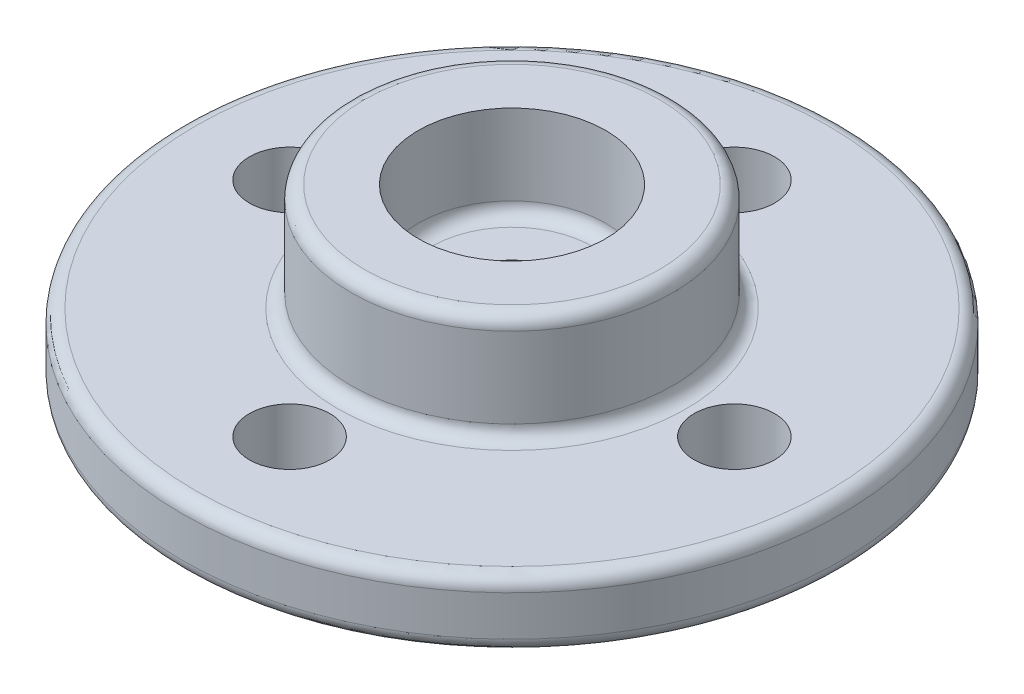
SolidWorks part; units mm, degrees
material "6061 Alloy"
ref_plane "Front Plane" through (0, 0, 0) normal (0, 0, 1) x (1, 0, 0)
ref_plane "Top Plane" through (0, 0, 0) normal (0, 1, 0) x (1, 0, 0)
ref_plane "Right Plane" through (0, 0, 0) normal (1, 0, 0) x (0, 0, -1)
sketch "Sketch1" plane through (0, 0, 0) normal (1, 0, 0) x (0, 0, -1)
  line L0 (1.5, 0) -> (1.5, 3)
  line L2 (13.53, 0) -> (-13.53, 0) construction
  line L3 (1.5, 3) -> (3.5, 3)
  line L4 (3.5, 3) -> (3.5, 6.5)
  line L5 (3.5, 6.5) -> (6, 6.5)
  line L7 (6, 6.5) -> (6, 2.5)
  line L8 (6, 2.5) -> (12.3, 2.5)
  line L9 (12.3, 2.5) -> (12.3, 0)
  line L10 (12.3, 0) -> (1.5, 0)
  line L11 (0, -5.7365) -> (0, 32.5513) construction
  line L12 (0, 3.575) -> (0, -3.575) construction
  dimension "D1" = 3.5
  dimension "D2" = 1.5
  dimension "D3" = 12.3
  dimension "D4" = 6
  dimension "D5" = 2.5
  dimension "D6" = 4
  dimension "D7" = 3.5
revolve "Revolve1" add sketch "Sketch1" angle 360 about L11
sketch "Sketch2" plane through (0, 0, 0) normal (0, -1, 0) x (1, 0, 0)
  line L0 (0, -3.575) -> (0, 3.575) construction
  line L1 (3.575, 0) -> (-3.575, 0) construction
  circle A0 centre (0, -8.3) radius 1.5
  dimension "D1" = 3
  dimension "D2" = 8.3
extrude "Cut-Extrude1" cut sketch "Sketch2" against normal blind 10
pattern_circular "CirPattern1" count 4 over 360 about axis through (0, 0, 0) along (0, 1, 0) of "Cut-Extrude1"
fillet "Fillet1" radius 0.5 5 edges at (0, 0, -12.3) (0, 2.5, -12.3) (0, 6.5, -6) (0, 3, -3.5) (0, 2.5, -6)
